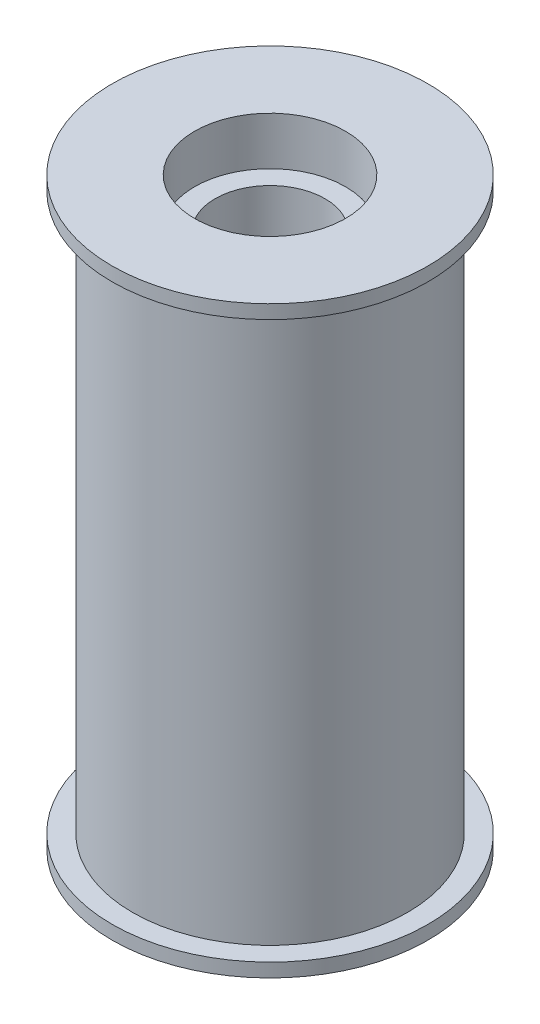
SolidWorks part; units mm, degrees
ref_plane "Front Plane" through (0, 0, 0) normal (0, 0, 1) x (1, 0, 0)
ref_plane "Top Plane" through (0, 0, 0) normal (0, 1, 0) x (1, 0, 0)
ref_plane "Right Plane" through (0, 0, 0) normal (1, 0, 0) x (0, 0, -1)
sketch "Esquisse1" plane through (0, 0, 0) normal (0, 1, 0) x (1, 0, 0)
  circle A0 centre (0, 0) radius 20
  dimension "D1" = 40
extrude "Boss.-Extru.1" add sketch "Esquisse1" along normal blind 85 contours A0
sketch "Esquisse6" plane through (0, 0, 0) normal (0, -1, 0) x (1, 0, 0)
  circle A0 centre (0, 0) radius 8
extrude "Enlèv. mat.-Extru.1" cut sketch "Esquisse6" against normal blind 85
sketch "Esquisse7" plane through (0, 0, 0) normal (0, -1, 0) x (1, 0, 0)
  circle A0 centre (0, 0) radius 11
extrude "Enlèv. mat.-Extru.2" cut sketch "Esquisse7" against normal blind 7
ref_plane "Plan1" through (0, 42.5, 0) normal (0, 1, 0) x (1, 0, 0)
mirror "Symétrie1" about plane through (0, 42.5, 0) normal (0, 1, 0) of "Enlèv. mat.-Extru.2"
ref_plane "Plan2" through (0, 0, 0) normal (1, 0, 0) x (0, 0, -1)
sketch "Esquisse11" plane through (0, 0, 0) normal (1, 0, 0) x (0, 0, -1)
  line L1 (19.9854, 0) -> (22.9854, 0)
  line L2 (19.9854, 0) -> (19.9854, 2)
  line L3 (19.9854, 2) -> (22.9854, 2)
  line L4 (22.9854, 0) -> (22.9854, 2)
ref_axis "Axe1" through (0, 85, 0) along (0, -1, 0)
revolve "Révolution1" add sketch "Esquisse11" angle 360 about axis through (0, 85, 0) along (0, -1, 0)
mirror "Symétrie2" about plane through (0, 42.5, 0) normal (0, 1, 0) of "Révolution1"
